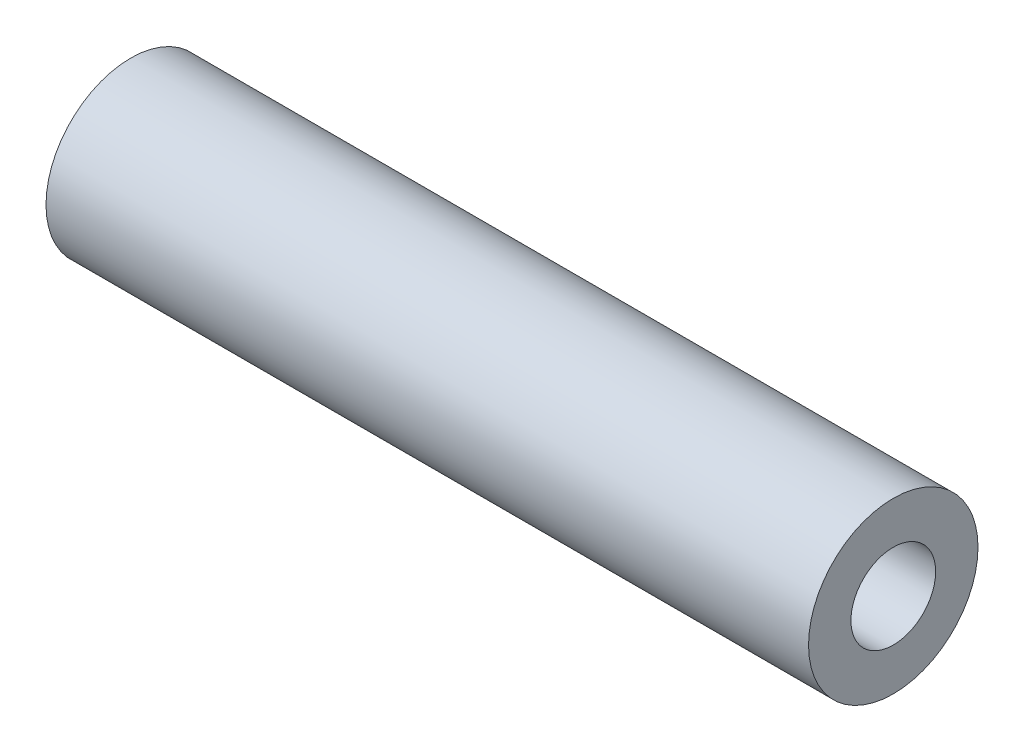
SolidWorks part; units mm, degrees
material "Alumina"
ref_plane "Front Plane" through (0, 0, 0) normal (0, 0, 1) x (1, 0, 0)
ref_plane "Top Plane" through (0, 0, 0) normal (0, 1, 0) x (1, 0, 0)
ref_plane "Right Plane" through (0, 0, 0) normal (1, 0, 0) x (0, 0, -1)
sketch "Sketch1" plane through (0, 0, 0) normal (1, 0, 0) x (0, 0, -1)
  circle A0 centre (0, 0) radius 6.35
  circle A1 centre (0, 0) radius 3.175
  dimension "D1" = 12.7
  dimension "D2" = 6.35
extrude "Alumina Tube Extrude" add sketch "Sketch1" along normal blind 57.15
equation "\"ID\"= .25"
equation "\"OD\"= .5"
equation "\"D2@Sketch1\"=\"ID\""
equation "\"D1@Sketch1\"=\"OD\""
equation "\"L\"=2.25"
equation "\"D1@Alumina Tube Extrude\"=\"L\""
